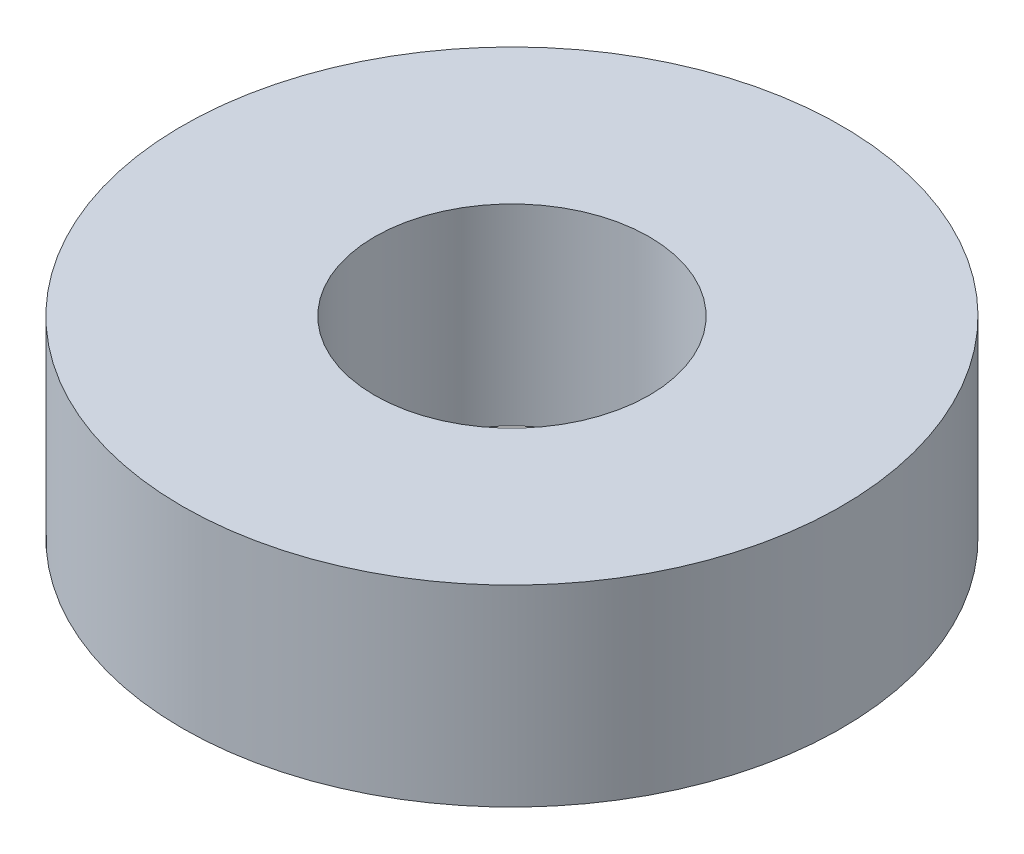
SolidWorks part; units mm, degrees
ref_plane "前视基准面" through (0, 0, 0) normal (0, 0, 1) x (1, 0, 0)
ref_plane "上视基准面" through (0, 0, 0) normal (0, 1, 0) x (1, 0, 0)
ref_plane "右视基准面" through (0, 0, 0) normal (1, 0, 0) x (0, 0, -1)
sketch "草图1" plane through (0, 0, 0) normal (0, 1, 0) x (1, 0, 0)
  circle A0 centre (0, 0) radius 5
  circle A1 centre (0, 0) radius 12
extrude "凸台-拉伸1" add sketch "草图1" along normal blind 7
